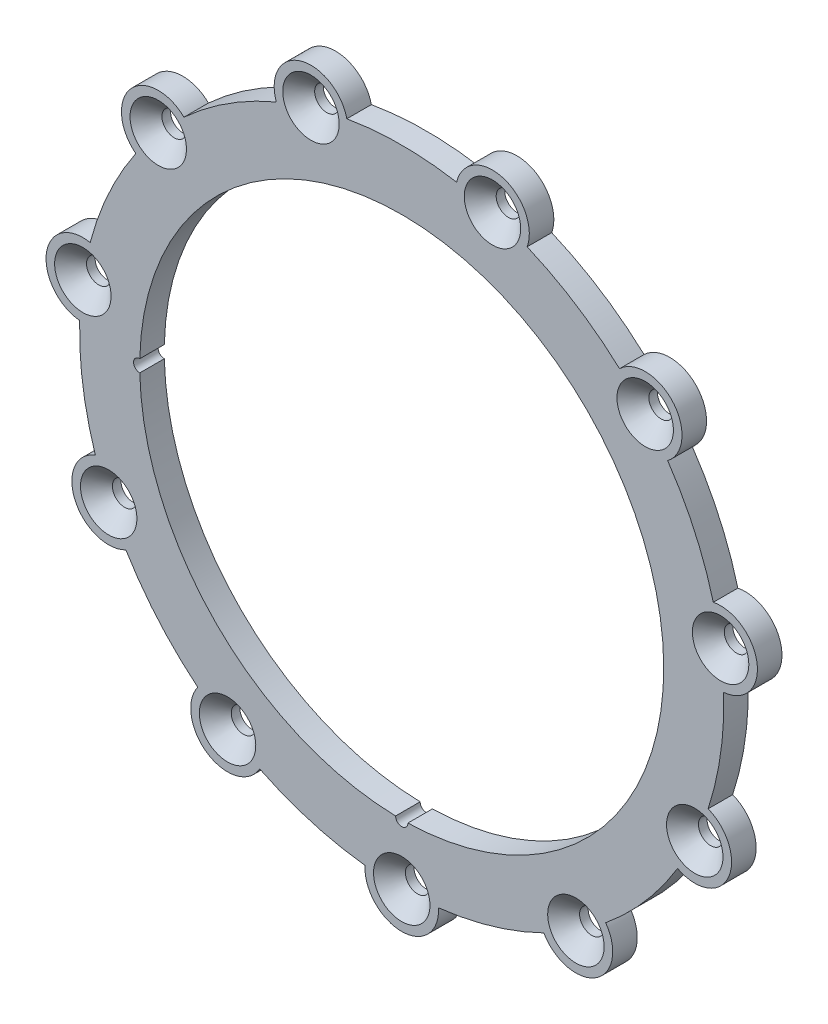
SolidWorks part; units mm, degrees
ref_plane "前视基准面" through (0, 0, 0) normal (0, 0, 1) x (1, 0, 0)
ref_plane "上视基准面" through (0, 0, 0) normal (0, 1, 0) x (1, 0, 0)
ref_plane "右视基准面" through (0, 0, 0) normal (1, 0, 0) x (0, 0, -1)
sketch "草图1" plane through (0, 0, 0) normal (0, 0, 1) x (1, 0, 0)
  line L0 (0, 0) -> (-51.9656, 7.4715) construction
  line L1 (-51.9656, 7.4715) -> (-73.6711, 10.5923) construction
  line L2 (0, 0) -> (-47.7557, -21.8093) construction
  line L3 (-47.7557, -21.8093) -> (-59.3488, -27.1037) construction
  circle A0 centre (0, 0) radius 42.7
  circle A1 centre (0, 0) radius 62.5 construction
  circle A2 centre (0, 0) radius 59 construction
  circle A19 centre (0, 0) radius 52.5 construction
  circle A23 centre (-51.9656, 7.4715) radius 2
  circle A103 centre (-47.7557, -21.8093) radius 6 construction
  circle A104 centre (-51.9656, 7.4715) radius 6 construction
  arc A105 (-57.9046, 8.3254) -> (-52.4788, 1.4935) centre (-51.9656, 7.4715) ccw
  arc A106 (-49.9322, -16.218) -> (-53.2135, -24.3018) centre (-47.7557, -21.8093) ccw
  arc A107 (-49.9322, -16.218) -> (-52.4788, 1.4935) centre (0, 0) cw
  arc A108 (-44.2114, 38.3094) -> (-43.3405, 29.6286) centre (-39.6769, 34.3802) ccw
  arc A109 (-50.7738, 13.352) -> (-43.3405, 29.6286) centre (0, 0) cw
  arc A110 (-50.7738, 13.352) -> (-57.9046, 8.3254) centre (-51.9656, 7.4715) ccw
  circle A111 centre (-39.6769, 34.3802) radius 2
  arc A112 (-16.4814, 56.1303) -> (-20.4419, 48.3568) centre (-14.791, 50.3734) ccw
  arc A113 (-35.495, 38.6828) -> (-20.4419, 48.3568) centre (0, 0) cw
  arc A114 (-35.495, 38.6828) -> (-44.2114, 38.3094) centre (-39.6769, 34.3802) ccw
  circle A115 centre (-14.791, 50.3734) radius 2
  arc A116 (16.4814, 56.1303) -> (8.9468, 51.732) centre (14.791, 50.3734) ccw
  arc A117 (-8.9468, 51.732) -> (8.9468, 51.732) centre (0, 0) cw
  arc A118 (-8.9468, 51.732) -> (-16.4814, 56.1303) centre (-14.791, 50.3734) ccw
  circle A119 centre (14.791, 50.3734) radius 2
  arc A120 (44.2114, 38.3094) -> (35.495, 38.6828) centre (39.6769, 34.3802) ccw
  arc A121 (20.4419, 48.3568) -> (35.495, 38.6828) centre (0, 0) cw
  arc A122 (20.4419, 48.3568) -> (16.4814, 56.1303) centre (14.791, 50.3734) ccw
  circle A123 centre (39.6769, 34.3802) radius 2
  arc A124 (57.9046, 8.3254) -> (50.7738, 13.352) centre (51.9656, 7.4715) ccw
  arc A125 (43.3405, 29.6286) -> (50.7738, 13.352) centre (0, 0) cw
  arc A126 (43.3405, 29.6286) -> (44.2114, 38.3094) centre (39.6769, 34.3802) ccw
  circle A131 centre (51.9656, 7.4715) radius 2
  arc A132 (53.2135, -24.3018) -> (49.9322, -16.218) centre (47.7557, -21.8093) ccw
  arc A133 (52.4788, 1.4935) -> (49.9322, -16.218) centre (0, 0) cw
  arc A134 (52.4788, 1.4935) -> (57.9046, 8.3254) centre (51.9656, 7.4715) ccw
  circle A135 centre (47.7557, -21.8093) radius 2
  arc A136 (31.6275, -49.2133) -> (33.2376, -40.6388) centre (28.3836, -44.1658) ccw
  arc A137 (44.9554, -27.1157) -> (33.2376, -40.6388) centre (0, 0) cw
  circle A191 centre (-47.7557, -21.8093) radius 2 construction
  circle A209 centre (14.791, 50.3734) radius 2 [skipped]
  circle A214 centre (39.6769, 34.3802) radius 2 [skipped]
  circle A220 centre (51.9656, 7.4715) radius 2 [skipped]
  circle A226 centre (47.7557, -21.8093) radius 2 [skipped]
  circle A232 centre (28.3836, -44.1658) radius 2 [skipped]
  circle A238 centre (0, -52.5) radius 2 [skipped]
  arc A243 (44.9554, -27.1157) -> (53.2135, -24.3018) centre (47.7557, -21.8093) ccw
  circle A244 centre (28.3836, -44.1658) radius 2
  arc A245 (0, -58.5) -> (5.9902, -52.1571) centre (0, -52.5) ccw
  arc A246 (23.159, -47.1159) -> (5.9902, -52.1571) centre (0, 0) cw
  arc A247 (23.159, -47.1159) -> (31.6275, -49.2133) centre (28.3836, -44.1658) ccw
  circle A248 centre (0, -52.5) radius 2
  arc A249 (-31.6275, -49.2133) -> (-23.159, -47.1159) centre (-28.3836, -44.1658) ccw
  circle A252 centre (-28.3836, -44.1658) radius 2 [skipped]
  arc A256 (-5.9902, -52.1571) -> (-23.159, -47.1159) centre (0, 0) cw
  circle A261 centre (-39.6769, 34.3802) radius 2 [skipped]
  circle A267 centre (-14.791, 50.3734) radius 2 [skipped]
  arc A269 (-5.9902, -52.1571) -> (0, -58.5) centre (0, -52.5) ccw
  circle A272 centre (-28.3836, -44.1658) radius 2
  arc A273 (-53.2135, -24.3018) -> (-44.9554, -27.1157) centre (-47.7557, -21.8093) ccw
  arc A274 (-33.2376, -40.6388) -> (-44.9554, -27.1157) centre (0, 0) cw
  arc A275 (-33.2376, -40.6388) -> (-31.6275, -49.2133) centre (-28.3836, -44.1658) ccw
  circle A276 centre (-47.7557, -21.8093) radius 2
  dimension "D1" = 85.4
  dimension "D2" = 11
  dimension "D3" = 118
  dimension "D6" = 105
  dimension "D5" = 11
extrude "凸台-拉伸1" add sketch "草图1" along normal blind 4
sketch "草图2" plane through (0, 0, 4) normal (0, 0, 1) x (1, 0, 0)
  circle A0 centre (0, -42.7) radius 1
  circle A1 centre (0, 0) radius 42.7 construction
  circle A3 centre (-42.7, 0) radius 1
extrude "切除-拉伸1" cut sketch "草图2" against normal blind 4
ref_point "点1"
sketch "草图4" plane through (0, 0, 0) normal (1, 0, 0) x (0, 0, -1)
  line L0 (-4, -52.5) -> (6.0274, -52.5) construction
  line L1 (-4, -52.5) -> (-4, -57.1)
  line L2 (-4, -52.1571) -> (-4, -58.5) construction
  line L3 (-4, -52.5) -> (-1.4, -52.5)
  line L4 (-1.4, -52.5) -> (-1.4, -54.5)
  line L5 (-1.4, -54.5) -> (-4, -57.1)
  dimension "D1" = 4.6
  dimension "D2" = 2.6
revolve "切除-旋转1" cut sketch "草图4" angle 360 about L0
pattern_circular "阵列(圆周)1" count 11 every 32.727 about axis through (0, 0, 0) along (0, 0, 1) of "切除-旋转1"
equation "\"52.5×2\"=96.9638"
